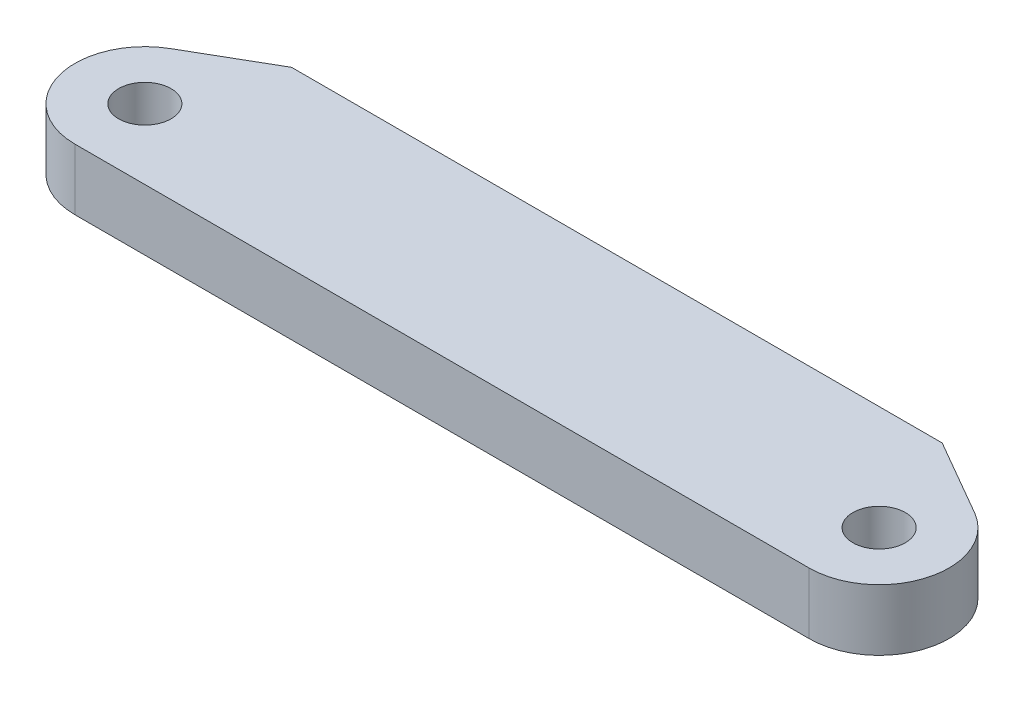
SolidWorks part; units mm, degrees
ref_plane "Front Plane" through (0, 0, 0) normal (0, 0, 1) x (1, 0, 0)
ref_plane "Top Plane" through (0, 0, 0) normal (0, 1, 0) x (1, 0, 0)
ref_plane "Right Plane" through (0, 0, 0) normal (1, 0, 0) x (0, 0, -1)
sketch "Sketch1" plane through (0, 0, 0) normal (0, 1, 0) x (1, 0, 0)
  line L0 (0, 5) -> (0, -5) construction
  line L1 (-18.6077, -5) -> (18.6077, -5)
  line L2 (-18.6077, -5) -> (-18.6077, 5) construction
  line L3 (-18.6077, 5) -> (18.6077, 5)
  line L4 (18.6077, -5) -> (18.6077, 5) construction
  line L5 (-18.6077, -5) -> (18.6077, 5) construction
  line L6 (-18.6077, 5) -> (18.6077, -5) construction
  line L7 (-18.6077, 5) -> (-23, 2.4641)
  line L8 (-21, -5) -> (-18.6077, -5)
  line L9 (21, -5) -> (18.6077, -5)
  line L10 (18.6077, 5) -> (23, 2.4641)
  arc A0 (-23, 2.4641) -> (-21, -5) centre (-21, -1) ccw
  arc A1 (23, 2.4641) -> (21, -5) centre (21, -1) cw
  point P0 (0, 0)
  dimension "D2" = 4
  dimension "D1" = 10
  dimension "D3" = 60
  dimension "D4" = 42
extrude "Boss-Extrude1" add sketch "Sketch1" along normal blind 3.5
sketch "Sketch2" plane through (0, 3.5, 0) normal (0, 1, 0) x (1, 0, 0)
  circle A0 centre (-21, -1) radius 1.5
  arc A1 (-23, 2.4641) -> (-21, -5) centre (-21, -1) ccw construction
  circle A2 centre (21, -1) radius 1.5
  arc A3 (21, -5) -> (23, 2.4641) centre (21, -1) ccw construction
  dimension "D1" = 3
extrude "Cut-Extrude1" cut sketch "Sketch2" against normal through all
